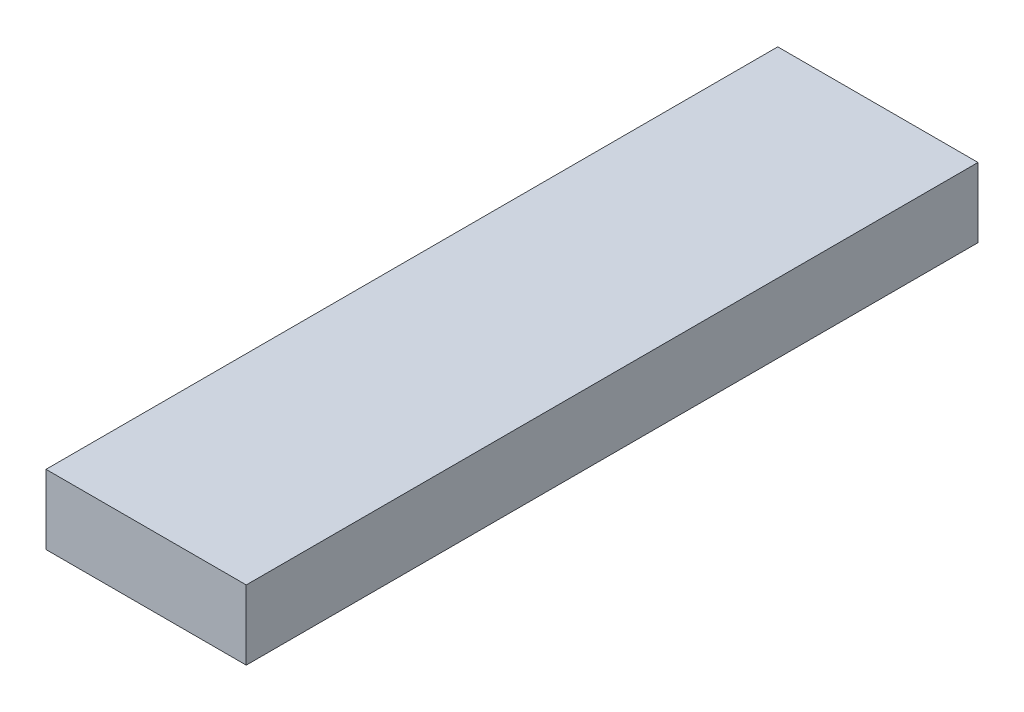
SolidWorks part; units mm, degrees
material "Polyurethane Foam Rigid"
ref_plane "X-Y Datum" through (0, 0, 0) normal (0, 0, 1) x (1, 0, 0)
ref_plane "X-Z Datum" through (0, 0, 0) normal (0, 1, 0) x (1, 0, 0)
ref_plane "Y-Z Datum" through (0, 0, 0) normal (1, 0, 0) x (0, 0, -1)
sketch "Sketch1" plane through (0, 0, 0) normal (0, 0, 1) x (1, 0, 0)
  line L1 (-27.4472, -9.525) -> (27.4472, -9.525)
  line L2 (-27.4472, -9.525) -> (-27.4472, 9.525)
  line L3 (-27.4472, 9.525) -> (27.4472, 9.525)
  line L4 (27.4472, -9.525) -> (27.4472, 9.525)
  line L5 (-27.4472, -9.525) -> (27.4472, 9.525) construction
  line L6 (-27.4472, 9.525) -> (27.4472, -9.525) construction
  point P0 (0, 0)
  dimension "D1" = 19.05
extrude "Boss-Extrude1" add sketch "Sketch1" along normal blind 200.599
